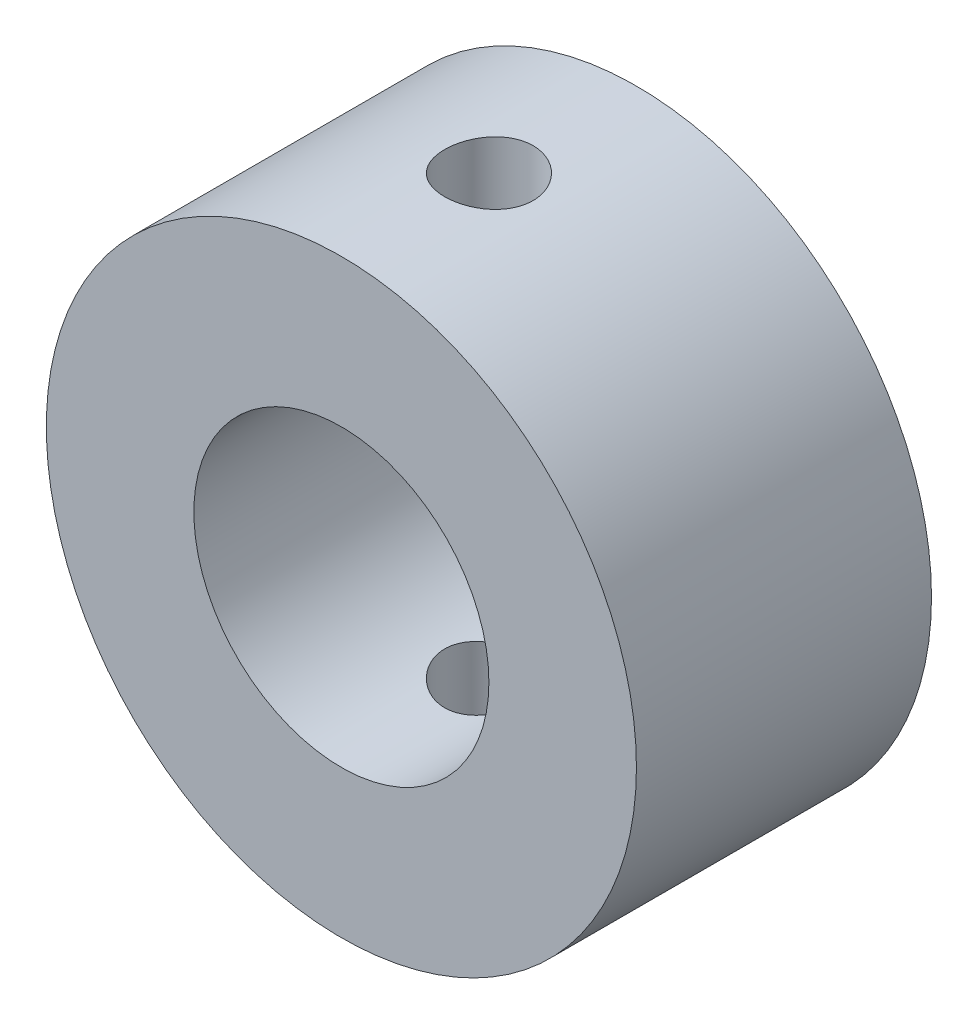
SolidWorks part; units mm, degrees
ref_plane "Front Plane" through (0, 0, 0) normal (0, 0, 1) x (1, 0, 0)
ref_plane "Top Plane" through (0, 0, 0) normal (0, 1, 0) x (1, 0, 0)
ref_plane "Right Plane" through (0, 0, 0) normal (1, 0, 0) x (0, 0, -1)
sketch "Sketch1" plane through (0, 0, 0) normal (0, 0, 1) x (1, 0, 0)
  circle A0 centre (0, 0) radius 20
  circle A1 centre (0, 0) radius 10
  dimension "D1" = 40
  dimension "D2" = 20
extrude "Boss-Extrude1" add sketch "Sketch1" along normal blind 20
sketch "Sketch2" plane through (0, 0, 0) normal (0, 1, 0) x (1, 0, 0)
  line L0 (20, 0) -> (-20, 0) construction
  circle A0 centre (0, -10) radius 3
  point P2 (0, 0)
  point P5 (0, 0)
  dimension "D1" = 6
  dimension "D2" = 10
extrude "Cut-Extrude1" cut sketch "Sketch2" against normal mid plane 56
